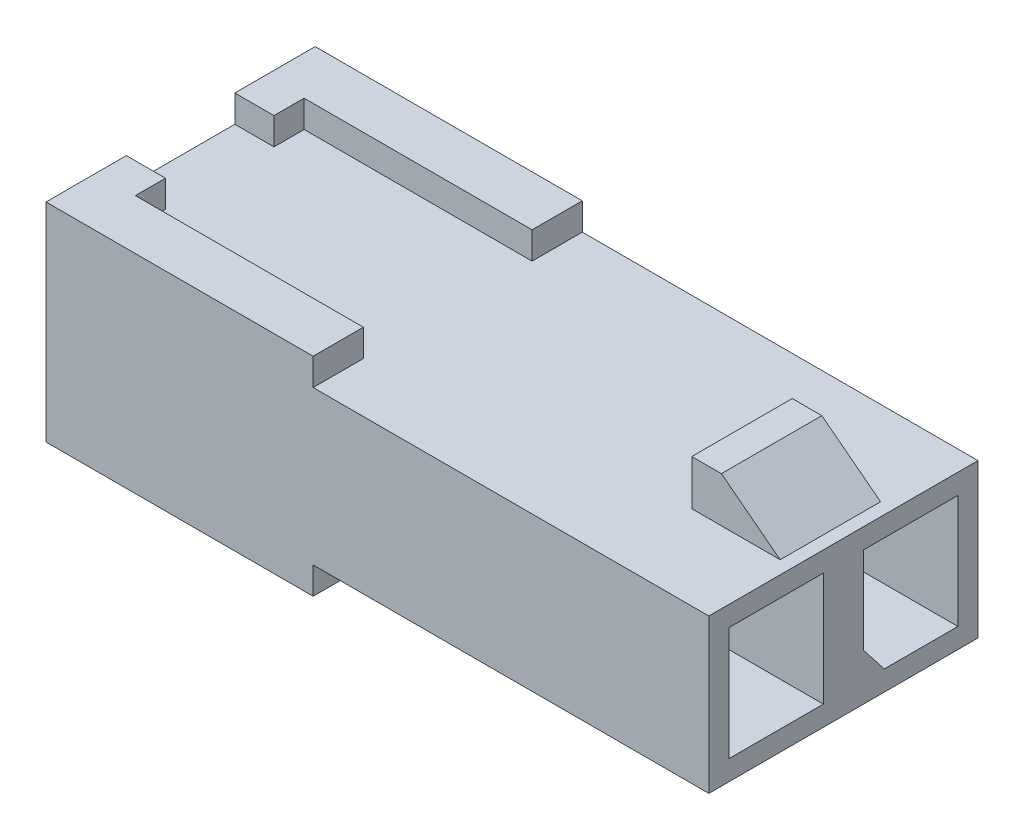
SolidWorks part; units mm, degrees
ref_plane "Front Plane" through (0, 0, 0) normal (0, 0, 1) x (1, 0, 0)
ref_plane "Top Plane" through (0, 0, 0) normal (0, 1, 0) x (1, 0, 0)
ref_plane "Right Plane" through (0, 0, 0) normal (1, 0, 0) x (0, 0, -1)
sketch "Sketch1" plane through (0, 0, 0) normal (1, 0, 0) x (0, 0, -1)
  line L0 (0, 1.9431) -> (0, -1.9431)
  line L1 (0, -1.9431) -> (-3.4036, -1.9431)
  line L2 (-3.4036, -1.9431) -> (-3.4036, 1.9431)
  line L3 (-3.4036, 1.9431) -> (0, 1.9431)
  dimension "D1" = 3.8862
  dimension "D2" = 3.4036
extrude "Extrude1" add sketch "Sketch1" along normal blind 16.764
sketch "Sketch2" plane through (0, 1.9431, 0) normal (0, 1, 0) x (1, 0, 0)
  line L0 (0, -3.4036) -> (6.7564, -3.4036)
  line L1 (16.764, -3.4036) -> (0, -3.4036) construction
  line L2 (6.7564, -3.4036) -> (6.7564, -2.1336)
  line L3 (6.7564, -2.1336) -> (0.9906, -2.1336)
  line L4 (0.9906, -2.1336) -> (0.9906, -1.3716)
  line L5 (0.9906, -1.3716) -> (0, -1.3716)
  line L7 (0, -1.3716) -> (0, -3.4036)
  dimension "D1" = 0.9906
  dimension "D2" = 6.7564
  dimension "D3" = 1.27
  dimension "D4" = 2.032
extrude "Extrude2" add sketch "Sketch2" along normal blind 0.6858
sketch "Sketch3" plane through (0, -1.9431, 0) normal (0, -1, 0) x (1, 0, 0)
  line L0 (0, 3.4036) -> (6.7564, 3.4036)
  line L1 (16.764, 3.4036) -> (0, 3.4036) construction
  line L2 (6.7564, 3.4036) -> (6.7564, 2.1336)
  line L3 (6.7564, 2.1336) -> (0.9906, 2.1336)
  line L4 (0.9906, 2.1336) -> (0.9906, 0)
  line L5 (16.764, 0) -> (0, 0) construction
  line L6 (0.9906, 0) -> (0, 0)
  line L7 (0, 0) -> (0, 3.4036)
  line L8 (0.9906, 2.1336) -> (0.9906, 1.3716) construction
  line L9 (6.7564, 2.1336) -> (0.9906, 2.1336) construction
  line L10 (6.7564, 3.4036) -> (6.7564, 2.1336) construction
extrude "Extrude3" add sketch "Sketch3" along normal blind 0.6858
sketch "Sketch4" plane through (0, 0, 0) normal (0, 0, 1) x (1, 0, 0)
  line L0 (16.4338, 1.9431) -> (14.9479, 3.0861)
  line L1 (14.9479, 3.0861) -> (14.1986, 3.0861)
  line L2 (14.1986, 3.0861) -> (14.1986, 1.9431)
  line L3 (16.764, 1.9431) -> (0, 1.9431) construction
  line L4 (14.1986, 1.9431) -> (16.4338, 1.9431)
  dimension "D1" = 0.7493
  dimension "D2" = 1.143
  dimension "D3" = 2.2352
  dimension "D4" = 0.3302
extrude "Extrude4" add sketch "Sketch4" along normal blind 1.27
sketch "Sketch5" plane through (16.764, 0, 0) normal (1, 0, 0) x (0, 0, -1)
  line L0 (-3.4036, -1.9431) -> (0, -1.9431) construction
  line L1 (-2.8956, 1.4351) -> (-0.508, 1.4351)
  line L2 (-2.8956, 1.4351) -> (-2.8956, -1.4351)
  line L3 (-2.8956, -1.4351) -> (-0.508, -1.4351)
  line L4 (-0.508, 1.4351) -> (-0.508, -1.4351)
  line L5 (-3.4036, 1.9431) -> (-3.4036, -1.9431) construction
  line L6 (0, -1.9431) -> (0, 1.9431) construction
  line L7 (0, 1.9431) -> (-3.4036, 1.9431) construction
  dimension "D1" = 0.508
  dimension "D2" = 0.508
  dimension "D3" = 0.508
  dimension "D4" = 0.508
extrude "Extrude5" cut sketch "Sketch5" against normal blind 9.906
sketch "Sketch6" plane through (0, 0, 0) normal (-1, 0, 0) x (0, 0, 1)
  line L1 (0.2032, 1.2065) -> (2.7432, 1.2065)
  line L2 (0.2032, 1.2065) -> (0.2032, -1.3335)
  line L3 (0.2032, -1.3335) -> (2.7432, -1.3335)
  line L4 (2.7432, 1.2065) -> (2.7432, -1.3335)
  line L5 (0, -2.6289) -> (0, 1.9431) construction
  line L6 (1.3716, 2.6289) -> (3.4036, 2.6289) construction
  dimension "D1" = 2.54
  dimension "D2" = 0.2032
  dimension "D3" = 1.4224
  dimension "D4" = 2.54
extrude "Extrude6" cut sketch "Sketch6" against normal blind 6.35
mirror "Mirror1" of "Extrude5", "Extrude6", "Extrude4", "Extrude3", "Extrude2", "Extrude1"
sketch "Sketch7" plane through (6.858, 0, 0) normal (1, 0, 0) x (0, 0, -1)
  line L0 (0.508, -0.7627) -> (1.0332, -1.4351)
  line L1 (0.508, -1.4351) -> (0.508, 1.4351) construction
  line L2 (2.8956, -1.4351) -> (0.508, -1.4351) construction
  line L3 (1.0332, -1.4351) -> (0.508, -1.4351)
  line L4 (0.508, -1.4351) -> (0.508, -0.7627)
extrude "Extrude7" add sketch "Sketch7" along normal blind 9.906
